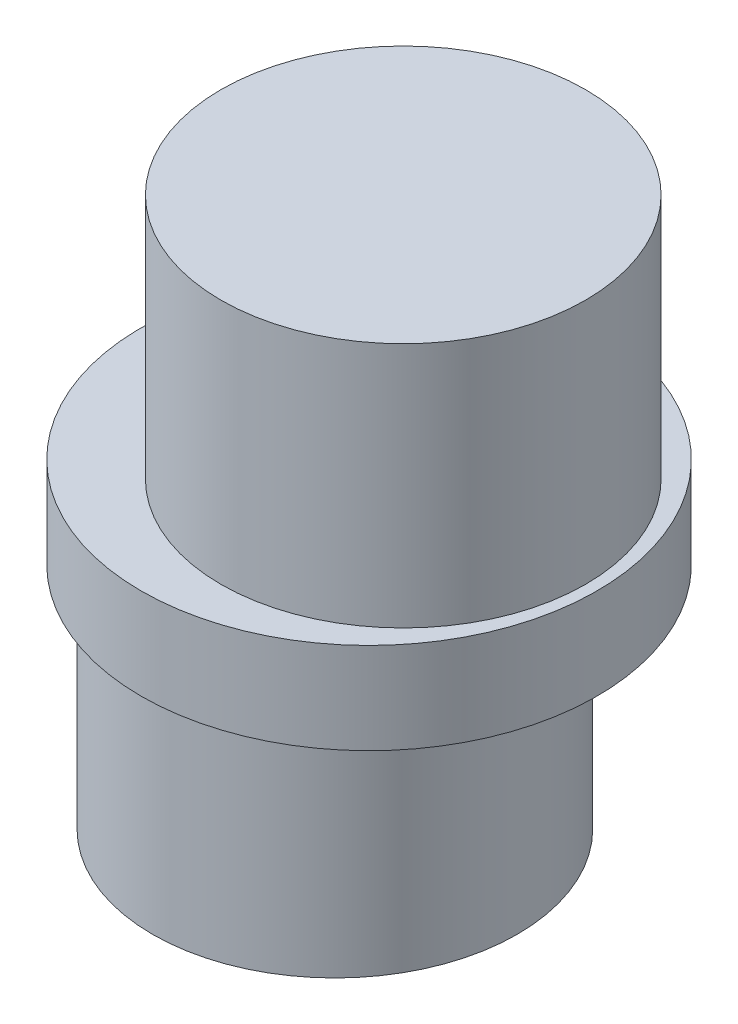
SolidWorks part; units mm, degrees
ref_plane "Front Plane" through (0, 0, 0) normal (0, 0, 1) x (1, 0, 0)
ref_plane "Top Plane" through (0, 0, 0) normal (0, 1, 0) x (1, 0, 0)
ref_plane "Right Plane" through (0, 0, 0) normal (1, 0, 0) x (0, 0, -1)
sketch "Sketch1" plane through (0, 0, 0) normal (0, 1, 0) x (1, 0, 0)
  circle A1 centre (0, 0) radius 7.5
  point P6 (0, 0)
  point P7 (0, 0)
  dimension "D1" = 15
extrude "Boss-Extrude1" add sketch "Sketch1" along normal blind 3 contours A1
sketch "Sketch2" plane through (0, 3, 0) normal (0, 1, 0) x (1, 0, 0)
  circle A0 centre (1.125, 0) radius 6
  circle A1 centre (0, 0) radius 7.5 construction
  dimension "D1" = 12
  dimension "D2" = 1.125
extrude "Boss-Extrude2" add sketch "Sketch2" along normal blind 8.1
sketch "Sketch3" plane through (0, 0, 0) normal (0, -1, 0) x (1, 0, 0)
  circle A0 centre (-1.125, 0) radius 6
  point P2 (0, 0)
  point P4 (0, 0)
  dimension "D1" = 12
  dimension "D2" = 1.125
extrude "Boss-Extrude3" add sketch "Sketch3" along normal blind 8.1
